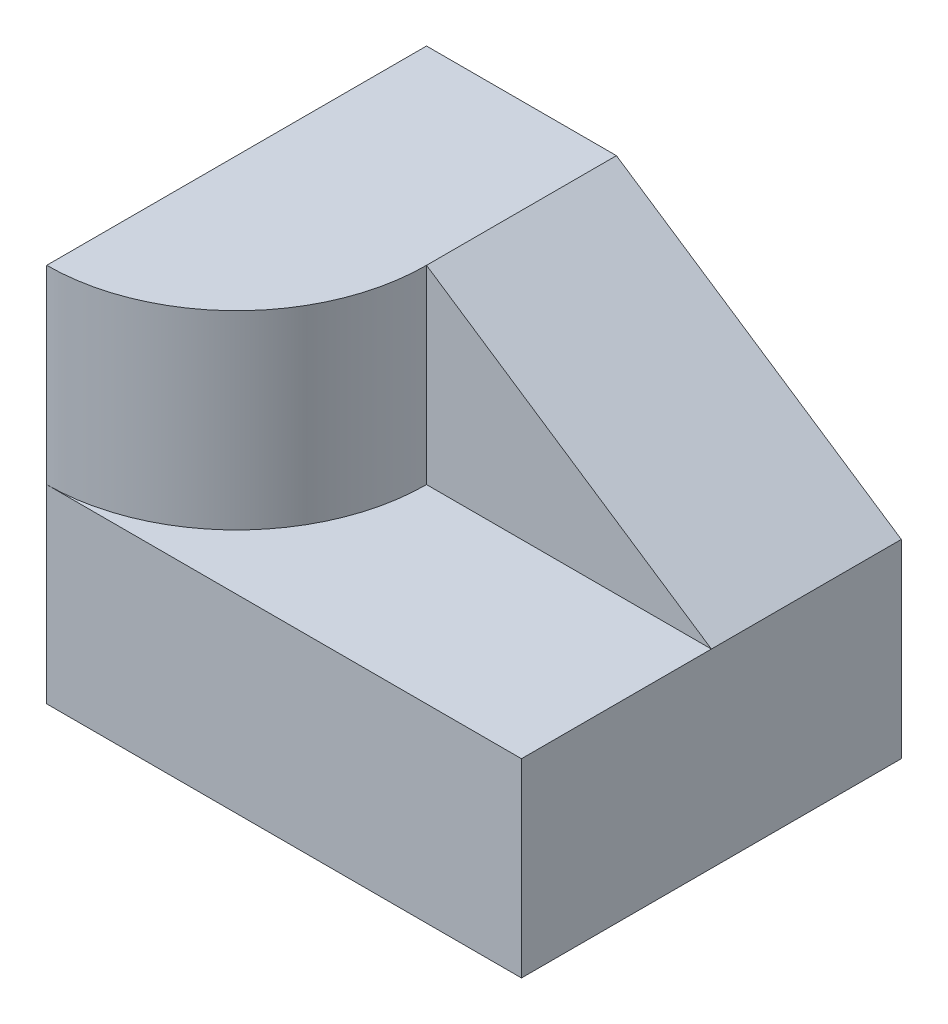
SolidWorks part; units mm, degrees
ref_plane "前基準面" through (0, 0, 0) normal (0, 0, 1) x (1, 0, 0)
ref_plane "上基準面" through (0, 0, 0) normal (0, 1, 0) x (1, 0, 0)
ref_plane "右基準面" through (0, 0, 0) normal (1, 0, 0) x (0, 0, -1)
sketch "草圖1" plane through (0, 0, 0) normal (0, 1, 0) x (1, 0, 0)
  line L1 (0, 0) -> (25, 0)
  line L2 (0, 0) -> (0, 20)
  line L3 (0, 20) -> (25, 20)
  line L4 (25, 0) -> (25, 20)
  dimension "D1" = 25
  dimension "D2" = 20
extrude "填料-伸長1" add sketch "草圖1" along normal blind 10
sketch "草圖2" plane through (0, 10, 0) normal (0, 1, 0) x (1, 0, 0)
  line L0 (0, 20) -> (0, 0) construction
  line L1 (0, 20) -> (0, 0)
  line L2 (0, 20) -> (10, 20)
  line L3 (25, 20) -> (0, 20) construction
  line L4 (10, 20) -> (10, 10)
  line L5 (0, 0) -> (25, 0) construction
  arc A0 (10, 10) -> (0, 0) centre (0, 10) cw
  dimension "D1" = 10
extrude "填料-伸長2" add sketch "草圖2" along normal blind 10
sketch "草圖3" plane through (0, 0, -20) normal (0, 0, -1) x (-1, 0, 0)
  line L0 (-10, 20) -> (-10, 10)
  line L1 (-10, 10) -> (-25, 10)
  line L2 (-25, 10) -> (-10, 20)
extrude "填料-伸長3" add sketch "草圖3" against normal blind 10
